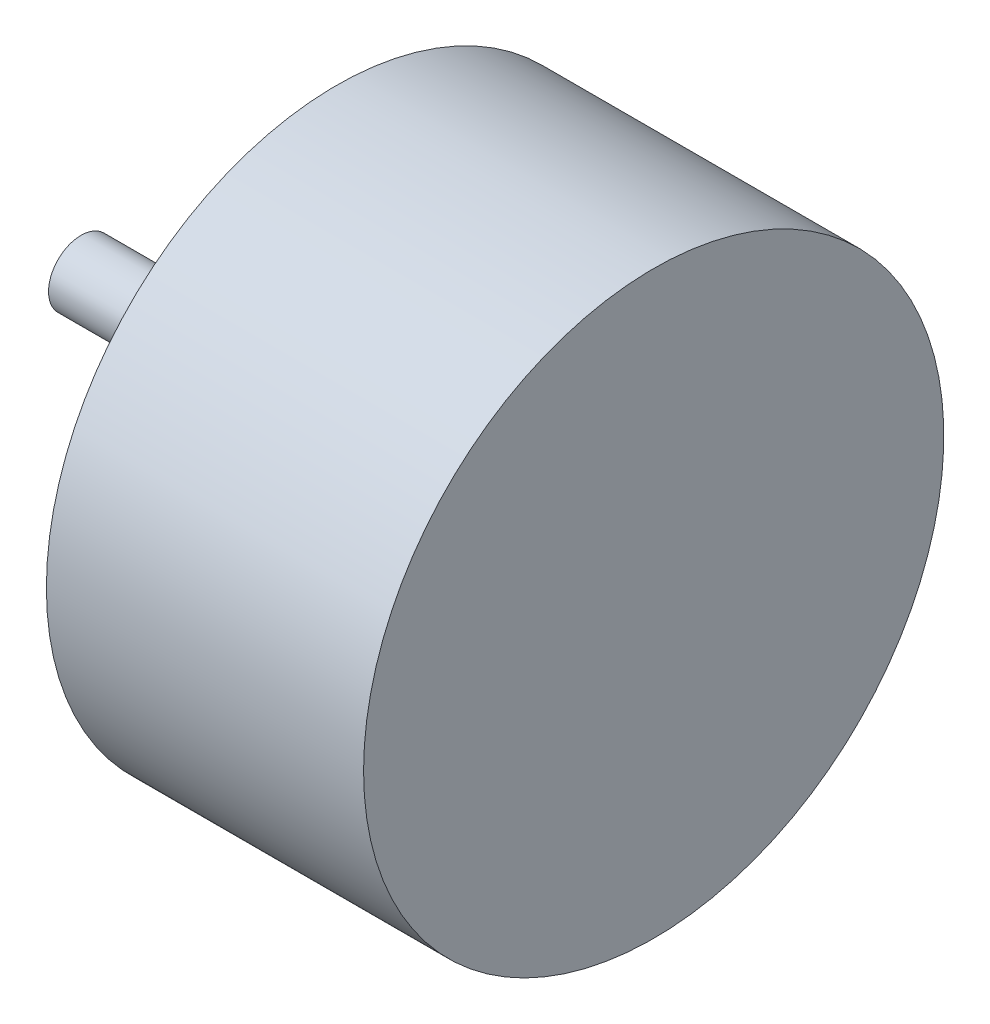
SolidWorks part; units mm, degrees
ref_plane "Front Plane" through (0, 0, 0) normal (0, 0, 1) x (1, 0, 0)
ref_plane "Top Plane" through (0, 0, 0) normal (0, 1, 0) x (1, 0, 0)
ref_plane "Right Plane" through (0, 0, 0) normal (1, 0, 0) x (0, 0, -1)
sketch "Sketch1" plane through (0, 0, 0) normal (0, 0, 1) x (1, 0, 0)
  line L0 (-5.9, 0) -> (20.55, 0)
  line L2 (-5.9, 0) -> (-5.9, 1.5)
  line L3 (-5.9, 1.5) -> (5.9, 1.5)
  line L5 (0, 0) -> (5.9, 1.5) construction
  line L6 (-5.9, 1.5) -> (0, 0) construction
  line L7 (20.55, 13.4) -> (5.9, 13.4)
  line L8 (20.55, 13.4) -> (20.55, 0)
  line L10 (5.9, 13.4) -> (5.9, 1.5)
  line L11 (20.55, 13.4) -> (13.225, 0) construction
  line L12 (13.225, 0) -> (5.9, 13.4) construction
  point P0 (0, 0)
  point P6 (13.225, 0)
  dimension "D2" = 11.8
  dimension "D3" = 26.45
revolve "Revolve1" add sketch "Sketch1" angle 360 about L0
